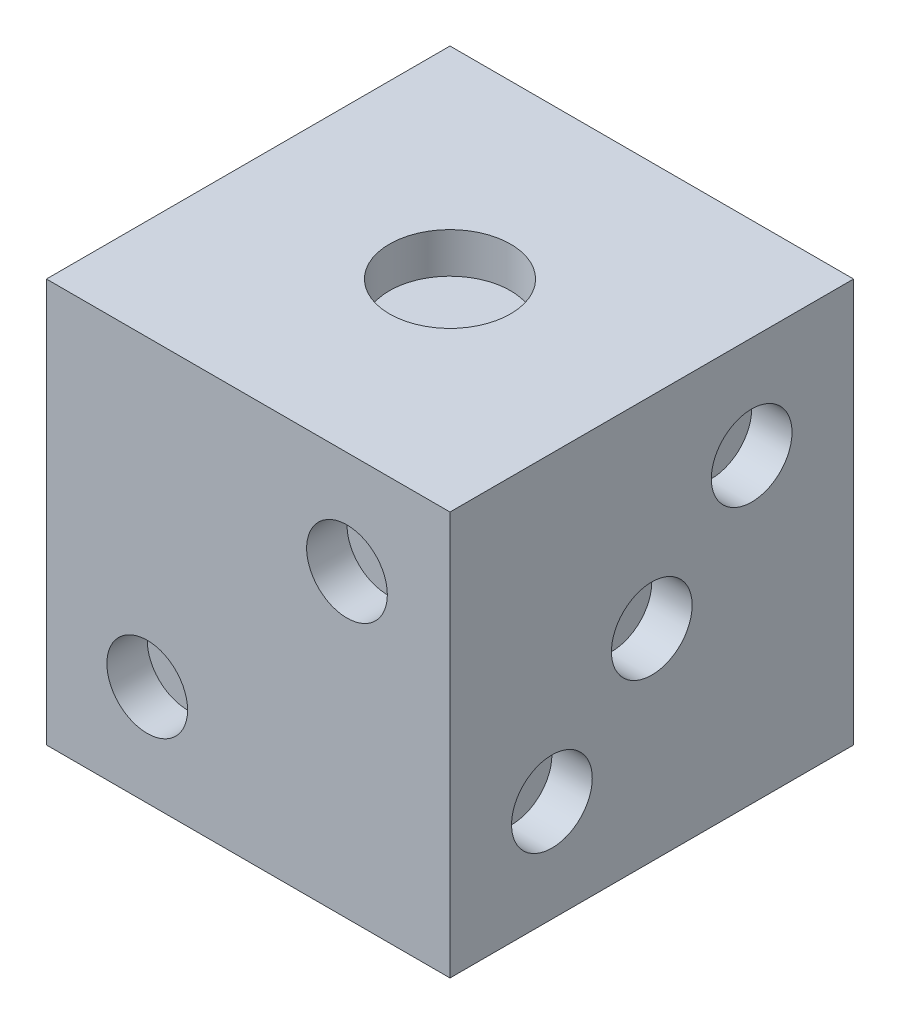
SolidWorks part; units mm, degrees
ref_plane "Front Plane" through (0, 0, 0) normal (0, 0, 1) x (1, 0, 0)
ref_plane "Top Plane" through (0, 0, 0) normal (0, 1, 0) x (1, 0, 0)
ref_plane "Right Plane" through (0, 0, 0) normal (1, 0, 0) x (0, 0, -1)
sketch "Sketch7" plane through (0, 0, 0) normal (0, 1, 0) x (1, 0, 0)
  line L1 (-50, 50) -> (50, 50)
  line L2 (-50, 50) -> (-50, -50)
  line L3 (-50, -50) -> (50, -50)
  line L4 (50, 50) -> (50, -50)
  point P4 (0, 0)
  point P5 (0, 0)
  point P6 (0, 0)
  point P7 (0, 0)
  dimension "D1" = 100
  dimension "D2" = 100
  dimension "D3" = 50
  dimension "D4" = 50
extrude "Boss-Extrude1" add sketch "Sketch7" along normal blind 100 contours L1 L4 L3 L2
sketch "Sketch8" plane through (0, 100, 0) normal (0, 1, 0) x (1, 0, 0)
  circle A0 centre (0, 0) radius 15
  dimension "D1" = 30
extrude "Cut-Extrude1" cut sketch "Sketch8" against normal blind 10
sketch "Sketch9" plane through (50, 0, 0) normal (1, 0, 0) x (0, 0, -1)
  line L0 (50, 100) -> (-50, 0) construction
  line L1 (50, 100) -> (50, 0) construction
  circle A0 centre (0, 50) radius 10
  circle A1 centre (24.7487, 74.7487) radius 10
  circle A2 centre (-24.7487, 25.2513) radius 10
  dimension "D1" = 20
  dimension "D2" = 35
  dimension "D3" = 35
extrude "Cut-Extrude2" cut sketch "Sketch9" against normal blind 10
sketch "Sketch10" plane through (0, 0, 50) normal (0, 0, 1) x (1, 0, 0)
  line L0 (-50, 0) -> (50, 100) construction
  circle A0 centre (-25.0235, 24.9765) radius 10
  circle A1 centre (24.474, 74.474) radius 10
  point P8 (0, 0)
  point P9 (-22.653, 27.347)
  point P10 (0, 0)
  point P11 (0, 0)
  point P12 (-25.0235, 24.9765)
  point P13 (-26.9198, 23.0802)
  point P14 (0, 0)
  point P15 (-24.1701, 25.8299)
  point P16 (-25.0235, 24.9765)
  dimension "D1" = 70
  dimension "D2" = 20
extrude "Cut-Extrude3" cut sketch "Sketch10" against normal blind 10
sketch "Sketch13" plane through (0, 0, 0) normal (0, -1, 0) x (-1, 0, 0)
  line L1 (-50, 50) -> (50, 50) construction
  line L2 (-50, 50) -> (-50, -50) construction
  line L3 (-50, -50) -> (50, -50) construction
  line L4 (50, 50) -> (50, -50) construction
  line L5 (-50, 50) -> (50, -50) construction
  line L6 (-50, -50) -> (50, 50) construction
  line L7 (25, -25) -> (-25, -25) construction
  line L8 (25, -25) -> (25, 25) construction
  line L9 (25, 25) -> (-25, 25) construction
  line L10 (-25, -25) -> (-25, 25) construction
  line L11 (25, -25) -> (-25, 25) construction
  line L12 (25, 25) -> (-25, -25) construction
  circle A0 centre (25, -25) radius 12.5
  circle A1 centre (-25, -25) radius 12.5
  circle A2 centre (25, 25) radius 12.5
  circle A3 centre (-25, 25) radius 12.5
  point P0 (0, 0)
  point P12 (0, 0)
  dimension "D2" = 25
  dimension "D1" = 50
extrude "Cut-Extrude4" cut sketch "Sketch13" against normal blind 10
sketch "Sketch14" plane through (0, 0, -50) normal (0, 0, -1) x (-1, 0, 0)
  line L0 (50, 100) -> (50, 0) construction
  line L1 (-50, 100) -> (50, 100) construction
  line L2 (-50, 100) -> (-50, 0) construction
  line L3 (-50, 0) -> (50, 0) construction
  line L4 (50, 100) -> (50, 0) construction
  line L5 (-50, 100) -> (50, 0) construction
  line L6 (-50, 0) -> (50, 100) construction
  line L8 (-25, 75) -> (25, 75) construction
  line L9 (-25, 75) -> (-25, 25) construction
  line L10 (-25, 25) -> (25, 25) construction
  line L11 (25, 75) -> (25, 25) construction
  line L12 (-25, 75) -> (25, 25) construction
  line L13 (-25, 25) -> (25, 75) construction
  circle A0 centre (25, 25) radius 12.5
  circle A1 centre (-25, 25) radius 12.5
  circle A2 centre (25, 75) radius 12.5
  circle A3 centre (-25, 75) radius 12.5
  circle A4 centre (0, 50) radius 12.5
  point P0 (0, 50)
  point P11 (0, 50)
  point P19 (0, 0)
  dimension "D2" = 25
  dimension "D1" = 50
extrude "Cut-Extrude5" cut sketch "Sketch14" against normal blind 10
sketch "Sketch16" plane through (-50, 0, 0) normal (-1, 0, 0) x (0, 0, 1)
  line L0 (50, 100) -> (50, 0) construction
  line L1 (50, 0) -> (-50, 0) construction
  line L2 (50, 0) -> (50, 100) construction
  line L3 (50, 100) -> (-50, 100) construction
  line L4 (-50, 0) -> (-50, 100) construction
  line L7 (-50, 0) -> (50, 0) construction
  line L8 (0, 100) -> (0, 0) construction
  line L9 (-50, 100) -> (50, 100) construction
  line L10 (-50, 75) -> (50, 75) construction
  line L11 (-50, 25) -> (50, 25) construction
  circle A6 centre (-35, 75) radius 12.5
  circle A7 centre (0, 75) radius 12.5
  circle A8 centre (35, 75) radius 12.5
  circle A9 centre (-35, 25) radius 12.5
  circle A10 centre (0, 25) radius 12.5
  circle A11 centre (35, 25) radius 12.5
  point P0 (0, 50)
  point P31 (0, 0)
  dimension "D4" = 35
  dimension "D2" = 25
  dimension "D5" = 35
  dimension "D6" = 35
  dimension "D7" = 35
  dimension "D1" = 25
  dimension "D3" = 25
sketch "Sketch17" plane through (-50, 0, 0) normal (-1, 0, 0) x (0, 0, 1)
extrude "Cut-Extrude11" cut sketch "Sketch16" against normal blind 10
